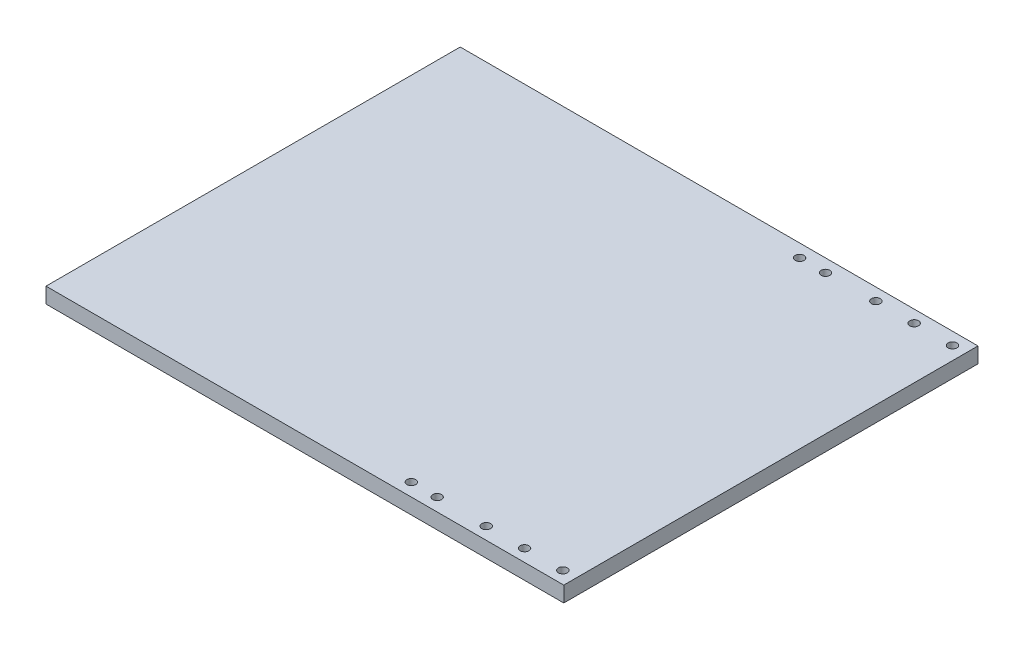
SolidWorks part; units mm, degrees
ref_plane "Front Plane" through (0, 0, 0) normal (0, 0, 1) x (1, 0, 0)
ref_plane "Top Plane" through (0, 0, 0) normal (0, 1, 0) x (1, 0, 0)
ref_plane "Right Plane" through (0, 0, 0) normal (1, 0, 0) x (0, 0, -1)
sketch "Sketch1" plane through (0, 0, 0) normal (0, 1, 0) x (1, 0, 0)
  line L1 (-100, -80) -> (100, -80)
  line L2 (-100, -80) -> (-100, 80)
  line L3 (-100, 80) -> (100, 80)
  line L4 (100, -80) -> (100, 80)
  line L5 (-100, -80) -> (100, 80) construction
  line L6 (-100, 80) -> (100, -80) construction
  point P0 (0, 0)
  dimension "D1" = 160
  dimension "D2" = 200
extrude "Boss-Extrude1" add sketch "Sketch1" along normal blind 6
hole_wizard "M3 Clearance Hole1" positions "Sketch2" profile "Sketch3" hole size "M3" standard "ISO" end condition through all
sketch "Sketch2" plane through (0, 6, 0) normal (0, 1, 0) x (1, 0, 0)
  point P0 (36.1, -75)
  point P3 (46.1, -75)
  point P15 (36.1, 75)
  point P18 (46.1, 75)
sketch "Sketch3" plane through (36.1, 6, 75) normal (1, 0, 0) x (0, 0, 1)
  line L0 (0, 0) -> (0, 6)
  line L1 (0, 6) -> (1.7, 6)
  line L2 (1.7, 6) -> (1.7, 0)
  line L5 (1.7, 0) -> (0, 0)
  line L11 (0, -6.35) -> (0, 107.95) construction
  dimension "Thru Hole Dia." = 3.4
  dimension "Thru Hole Depth" = 6
hole_wizard "M3 Clearance Hole2" positions "Sketch4" profile "Sketch5" hole size "M3" standard "ISO" end condition through all
sketch "Sketch4" plane through (0, 6, 0) normal (0, 1, 0) x (1, 0, 0)
  point P0 (94.9, -75.25)
  point P3 (80.1, -75.25)
  point P6 (65.3, -75.25)
  point P9 (94.9, 75.25)
  point P12 (80.1, 75.25)
  point P15 (65.3, 75.25)
sketch "Sketch5" plane through (94.9, 6, 75.25) normal (1, 0, 0) x (0, 0, 1)
  line L0 (0, 0) -> (0, 6)
  line L1 (0, 6) -> (1.7, 6)
  line L2 (1.7, 6) -> (1.7, 0)
  line L5 (1.7, 0) -> (0, 0)
  line L11 (0, -6.35) -> (0, 107.95) construction
  dimension "Thru Hole Dia." = 3.4
  dimension "Thru Hole Depth" = 6
